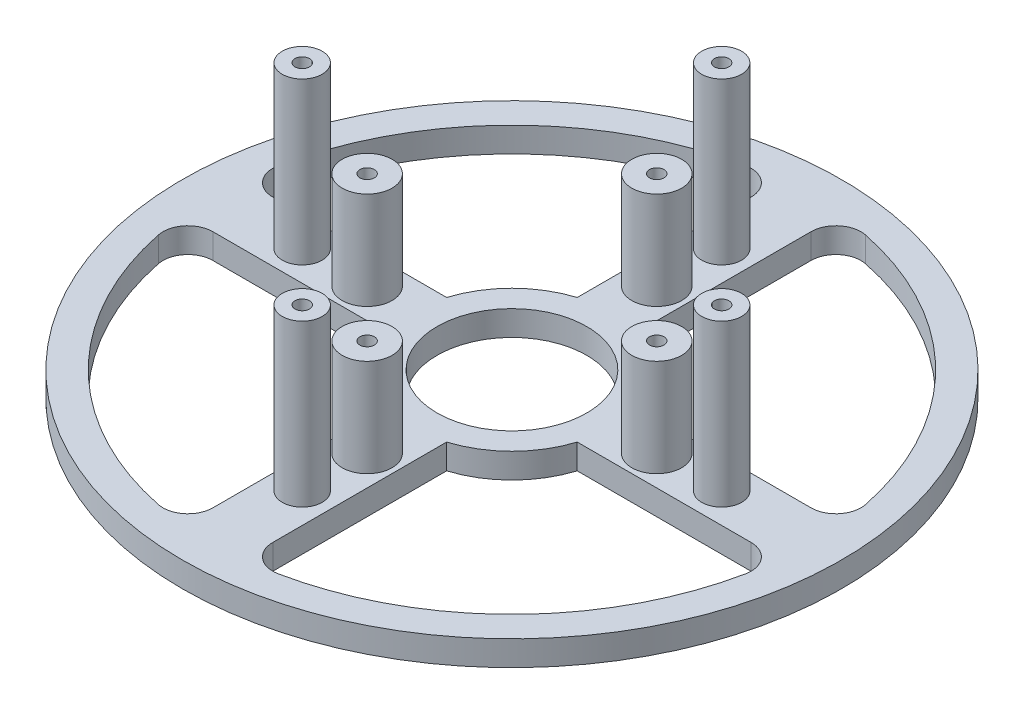
SolidWorks part; units mm, degrees
ref_plane "Front Plane" through (0, 0, 0) normal (0, 0, 1) x (1, 0, 0)
ref_plane "Top Plane" through (0, 0, 0) normal (0, 1, 0) x (1, 0, 0)
ref_plane "Right Plane" through (0, 0, 0) normal (1, 0, 0) x (0, 0, -1)
sketch "Sketch1" plane through (0, 0, 0) normal (0, 1, 0) x (1, 0, 0)
  line L0 (0, 0) -> (0, 66) construction
  line L1 (-6, -59.6992) -> (-6, -6)
  line L2 (6, -59.6992) -> (6, -6)
  line L3 (0, 0) -> (-50, 0) construction
  line L4 (-59.6992, -6) -> (-6, -6)
  line L5 (-59.6992, 6) -> (-6, 6)
  line L6 (6, 6) -> (6, 59.6992)
  line L7 (6, -6) -> (59.6992, -6)
  line L8 (-6, 6) -> (-6, 59.6992)
  line L9 (-6, -6) -> (-6, 6) construction
  line L10 (-6, 6) -> (6, 6) construction
  line L11 (6, 6) -> (59.6992, 6)
  circle A0 centre (0, 0) radius 66
  arc A1 (-6, 59.6992) -> (-59.6992, 6) centre (0, 0) ccw
  arc A2 (6, -59.6992) -> (59.6992, -6) centre (0, 0) ccw
  circle A3 centre (0, 31.6) radius 3 construction
  circle A4 centre (0, 0) radius 4 construction
  circle A5 centre (0, 0) radius 6 construction
  circle A6 centre (0, 31.6) radius 6 construction
  arc A7 (59.6992, 6) -> (6, 59.6992) centre (0, 0) ccw
  arc A8 (-59.6992, -6) -> (-6, -59.6992) centre (0, 0) ccw
  dimension "D1" = 6
  dimension "D2" = 132
  dimension "D3" = 6
  dimension "D4" = 8
  dimension "D6" = 2
  dimension "D5" = 31.6
extrude "Boss-Extrude1" add sketch "Sketch1" along normal blind 5
fillet "Fillet1" radius 5 12 edges at (-6, 2.5, 59.6992) (6, 2.5, 59.6992) (59.6992, 2.5, 6) (-6, 2.5, 6) (6, 2.5, 6) (-6, 2.5, -6) (6, 2.5, -6) (59.6992, 2.5, -6) (-59.6992, 2.5, 6) (-59.6992, 2.5, -6) (6, 2.5, -59.6992) (-6, 2.5, -59.6992)
sketch "Sketch3" plane through (0, 5, 0) normal (0, 1, 0) x (1, 0, 0)
  line L0 (0, 0) -> (-29, 0) construction
  circle A0 centre (-29, 0) radius 5
  dimension "D1" = 10
  dimension "D2" = 29
extrude "Boss-Extrude3" add sketch "Sketch3" along normal blind 19.5
sketch "Sketch4" plane through (0, 5, 0) normal (0, 1, 0) x (1, 0, 0)
  circle A1 centre (0, 0) radius 20
  dimension "D1" = 40
extrude "Boss-Extrude4" add sketch "Sketch4" against normal up to surface (5 mm away) up to face at (25.6558, 0, 25.6558)
pattern_circular "CirPattern1" count 4 over 360 about axis through (0, 0, 0) along (0, 1, 0) of "Boss-Extrude3"
sketch "Sketch5" plane through (0, 5, 0) normal (0, 1, 0) x (1, 0, 0)
  circle A0 centre (0, 0) radius 15
  dimension "D1" = 30
extrude "Cut-Extrude1" cut sketch "Sketch5" against normal blind 10
sketch "Sketch6" plane through (0, 5, 0) normal (0, 1, 0) x (1, 0, 0)
  line L0 (0, 0) -> (-42, 0) construction
  circle A0 centre (-42, 0) radius 4
  circle A1 centre (-42, 0) radius 1.5 construction
  dimension "D2" = 8
  dimension "D3" = 3
  dimension "D1" = 42
extrude "Boss-Extrude5" add sketch "Sketch6" along normal blind 32.25
pattern_circular "CirPattern2" count 4 over 360 about axis through (0, 0, 0) along (0, 1, 0) of "Boss-Extrude5"
sketch "Sketch7" plane through (0, 24.5, 0) normal (0, 1, 0) x (1, 0, 0)
  circle A0 centre (-29, 0) radius 1.45
  circle A1 centre (-42, 0) radius 1.45
  circle A2 centre (-42, 0) radius 4 construction
  circle A3 centre (-29, 0) radius 5 construction
  dimension "D1" = 2.9
extrude "Cut-Extrude3" cut sketch "Sketch7" against normal blind 6 and the other way through all
pattern_circular "CirPattern3" count 4 over 360 about axis through (0, 0, 0) along (0, 1, 0) of "Cut-Extrude3"
